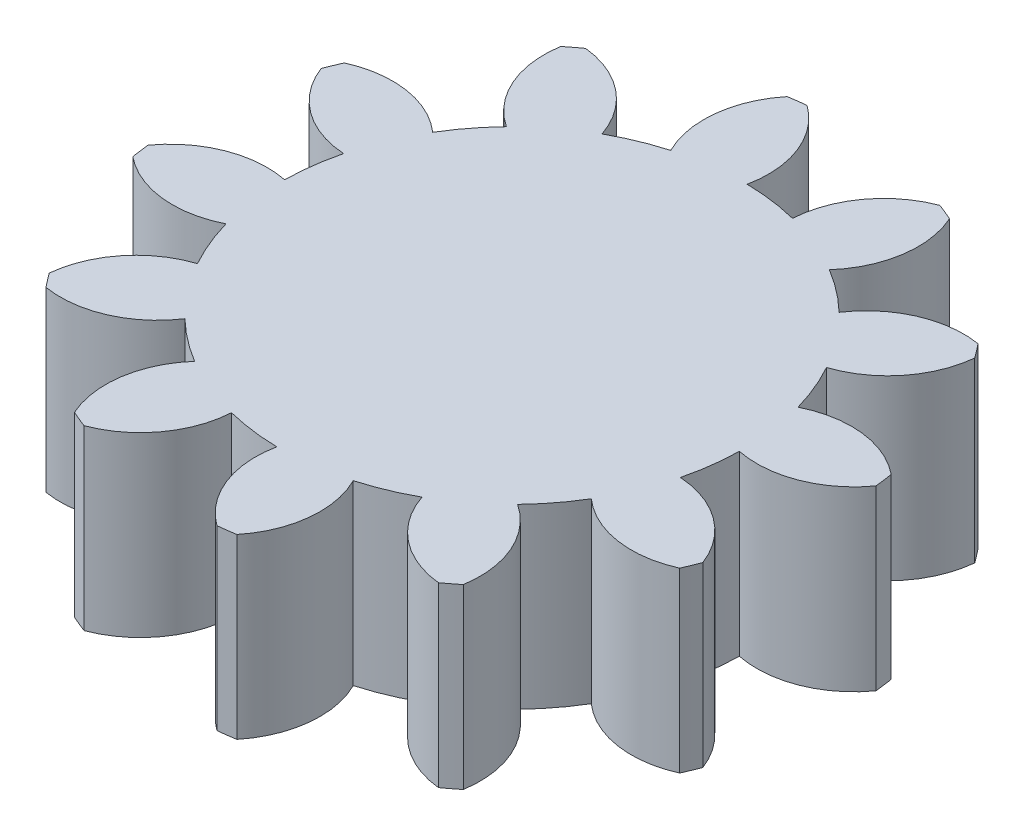
SolidWorks part; units mm, degrees
ref_plane "Front Plane" through (0, 0, 0) normal (0, 0, 1) x (1, 0, 0)
ref_plane "Top Plane" through (0, 0, 0) normal (0, 1, 0) x (1, 0, 0)
ref_plane "Right Plane" through (0, 0, 0) normal (1, 0, 0) x (0, 0, -1)
sketch "Sketch1" plane through (0, 0, 0) normal (0, 1, 0) x (1, 0, 0)
  circle A0 centre (0, 0) radius 5.6
  dimension "D1" = 11.2
extrude "Boss-Extrude1" add sketch "Sketch1" along normal blind 3
sketch "Sketch2" plane through (0, 3, 0) normal (0, 1, 0) x (1, 0, 0)
  line L0 (0, 0) -> (0, 4.8) construction
  line L1 (0, 4.8) -> (-1.5439, 4.2375) construction
  line L2 (-1.5439, 4.2375) -> (-0.0135, 0.037) construction
  line L3 (-0.8824, 5.3112) -> (-0.6265, 4.7589) construction
  line L4 (-0.6265, 4.7589) -> (0, 0) construction
  line L5 (0, 0) -> (0.5104, 3.8765) construction
  line L6 (0.5104, 3.8765) -> (0.7309, 5.5521)
  circle A0 centre (0, 0) radius 4.8 construction
  circle A1 centre (0, 0) radius 5.6 construction
  circle A2 centre (0, 0) radius 4.51 construction
  circle A3 centre (0, 0) radius 3.91 construction
  arc A4 (0.0662, 3.9094) -> (-0.582, 5.5697) centre (-1.5439, 4.2375) ccw
  arc A5 (0.5104, 3.8765) -> (0.0662, 3.9094) centre (0, 0) ccw
  arc A6 (0.7309, 5.5521) -> (-0.582, 5.5697) centre (0, 0) ccw
  circle M12 centre (0, 0) radius 5.6
  dimension "D1" = 11.2
  dimension "D2" = 9.6
  dimension "D3" = 9.02
  dimension "D4" = 7.82
  dimension "D5" = 20.018
  dimension "D6" = 0.6283
  dimension "D7" = 15
extrude "Cut-Extrude1" cut sketch "Sketch2" against normal blind 3 contours A5 L6 A4 M12
ref_plane "Plane1" through (0, 0, 0) normal (-0.9914, 0, -0.1305) x (-0.1305, 0, 0.9914)
mirror "Mirror1" about plane through (0, 0, 0) normal (-0.9914, 0, -0.1305) of "Cut-Extrude1"
pattern_circular "CirPattern1" count 12 over 360 about axis through (0, 0, 0) along (0, 1, 0) of "Cut-Extrude1", "Mirror1"
